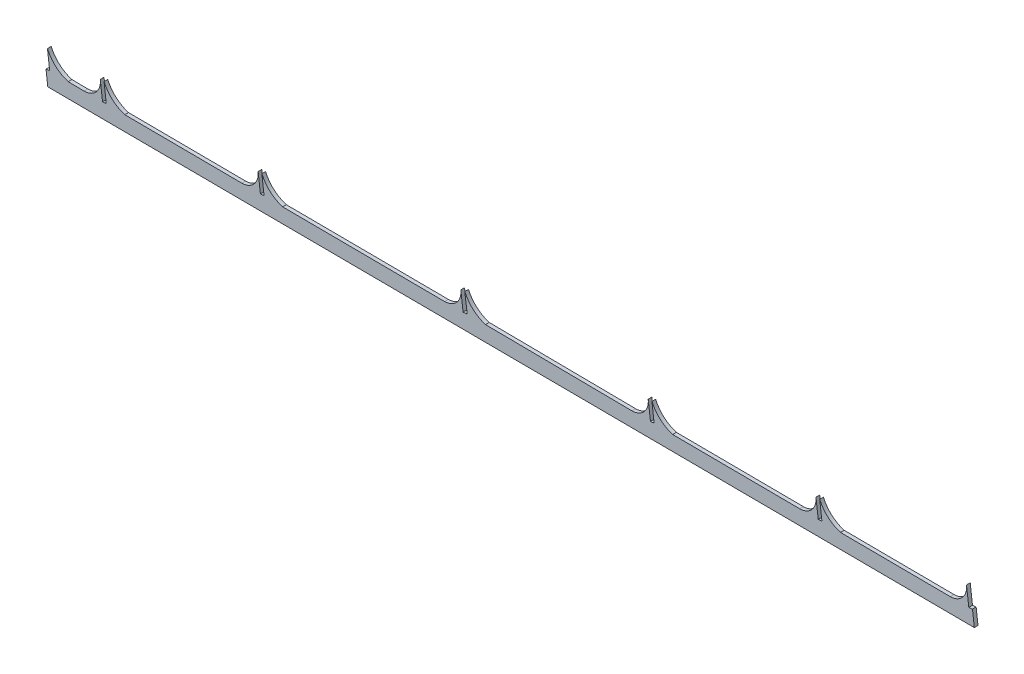
SolidWorks part; units mm, degrees
ref_plane "前视基准面" through (0, 0, 0) normal (0, 0, 1) x (1, 0, 0)
ref_plane "上视基准面" through (0, 0, 0) normal (0, 1, 0) x (1, 0, 0)
ref_plane "右视基准面" through (0, 0, 0) normal (1, 0, 0) x (0, 0, -1)
sketch "Model" plane through (0, 0, 0) normal (0, 0, 1) x (1, 0, 0)
  line L0 (465.7571, 9.4338) -> (-35.3111, 12.1687)
  line L2 (453.3695, 17.4358) -> (393.3708, 17.8357)
  line L3 (371.3546, 17.8841) -> (302.6341, 18.3309)
  line L4 (280.6179, 18.3794) -> (201.4274, 19.1853)
  line L5 (179.2953, 18.9324) -> (91.6854, 19.4823)
  line L6 (69.6692, 19.5307) -> (6.3281, 19.9482)
  line L7 (-15.6881, 19.9966) -> (-24.2697, 20.1152)
  line L8 (462.7673, 17.3731) -> (464.7523, 17.6169)
  line L9 (381.3504, 17.8621) -> (383.3355, 18.1059)
  line L10 (290.6093, 18.3939) -> (292.5944, 18.6376)
  line L11 (189.2895, 18.924) -> (191.5227, 19.1982)
  line L12 (79.6664, 19.4976) -> (81.6515, 19.7414)
  line L13 (-5.6886, 19.9443) -> (-3.7035, 20.188)
  line L14 (-34.2888, 20.2536) -> (-36.2739, 20.0099)
  line L15 (-35.4884, 30.0235) -> (-34.2888, 20.2536)
  line L16 (-36.2739, 20.0099) -> (-35.3111, 12.1687)
  line L17 (-6.907, 29.8675) -> (-5.6886, 19.9443)
  line L18 (-4.8906, 29.8565) -> (-3.7035, 20.188)
  line L19 (78.4504, 29.4016) -> (79.6664, 19.4976)
  line L20 (80.4667, 29.3906) -> (81.6515, 19.7414)
  line L21 (188.0765, 28.8033) -> (189.2895, 18.924)
  line L22 (190.2087, 29.0936) -> (191.5227, 19.1982)
  line L23 (289.3991, 28.2503) -> (290.6093, 18.3939)
  line L24 (291.4154, 28.2392) -> (292.5944, 18.6376)
  line L25 (380.1357, 27.755) -> (381.3504, 17.8621)
  line L26 (382.1521, 27.744) -> (383.3355, 18.1059)
  line L27 (461.5471, 27.3107) -> (462.7673, 17.3731)
  line L28 (464.7523, 17.6169) -> (465.7571, 9.4338)
  arc A0 (452.7659, 17.4398) -> (461.5471, 27.3107) centre (452.727, 26.3157) ccw
  arc A1 (382.1521, 27.744) -> (393.3708, 17.8357) centre (398.4537, 34.8961) ccw
  arc A2 (371.3546, 17.8841) -> (380.1357, 27.755) centre (371.3157, 26.7601) ccw
  arc A3 (280.6179, 18.3794) -> (289.3991, 28.2503) centre (280.579, 27.2553) ccw
  arc A4 (179.2953, 18.9324) -> (188.0765, 28.8033) centre (179.2564, 27.8083) ccw
  arc A5 (69.6692, 19.5307) -> (78.4504, 29.4016) centre (69.6303, 28.4067) ccw
  arc A6 (-15.6881, 19.9966) -> (-6.907, 29.8675) centre (-15.7271, 28.8725) ccw
  arc A7 (291.4154, 28.2392) -> (302.6341, 18.3309) centre (307.717, 35.3913) ccw
  arc A8 (190.2087, 29.0936) -> (201.4274, 19.1853) centre (206.5103, 36.2457) ccw
  arc A9 (80.4667, 29.3906) -> (91.6854, 19.4823) centre (96.7683, 36.5427) ccw
  arc A10 (-4.8906, 29.8565) -> (6.3281, 19.9482) centre (11.4109, 37.0086) ccw
  arc A11 (-35.4884, 30.0235) -> (-24.2697, 20.1152) centre (-19.1868, 37.1756) ccw
extrude "凸台-拉伸1" add sketch "Model" along normal blind 2
